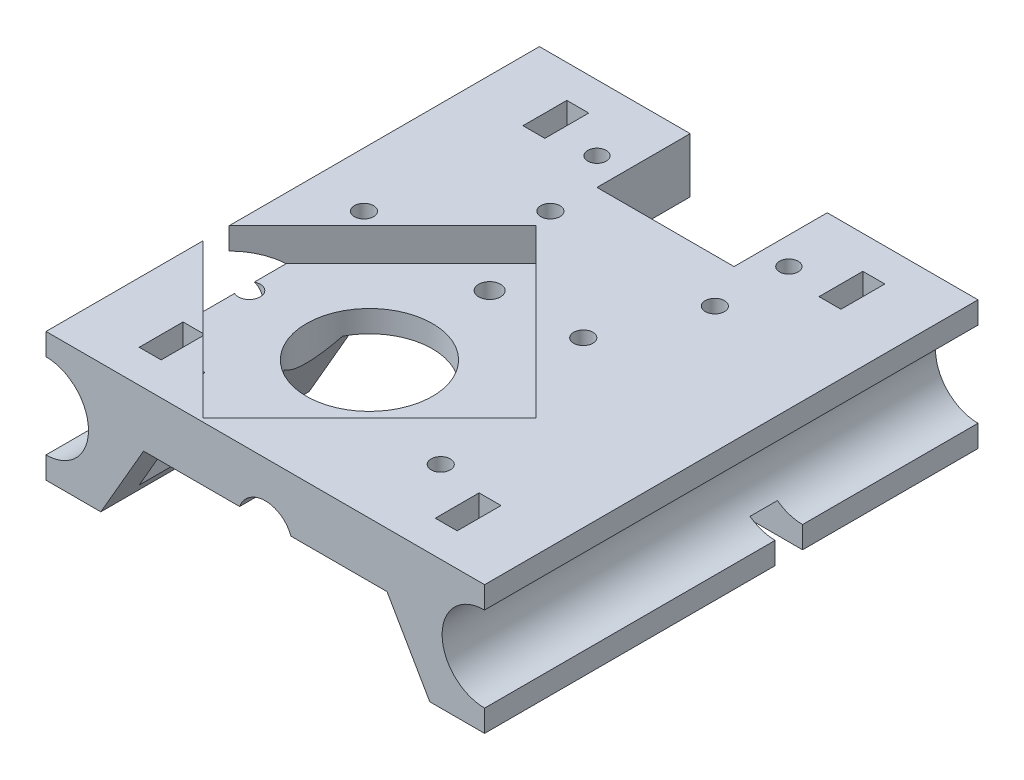
SolidWorks part; units mm, degrees
material "ABS"
ref_plane "Plano frontal" through (0, 0, 0) normal (0, 0, 1) x (1, 0, 0)
ref_plane "Plano superior" through (0, 0, 0) normal (0, 1, 0) x (1, 0, 0)
ref_plane "Plano direito" through (0, 0, 0) normal (1, 0, 0) x (0, 0, -1)
sketch "Esboço1" plane through (0, 0, 0) normal (0, 0, 1) x (1, 0, 0)
  line L0 (40, 0) -> (-40, 0)
  line L1 (-40, -19.5) -> (-40, -23.5)
  line L2 (-40, -23.5) -> (-30, -23.5)
  line L3 (-30, -23.5) -> (-22.2058, -10)
  line L4 (-22.2058, -10) -> (-4.6837, -10)
  line L5 (-40, 0) -> (-40, -4)
  line L6 (0, 0) -> (0, -46.1263) construction
  line L7 (40, 0) -> (40, -4)
  line L8 (30, -23.5) -> (22.2058, -10)
  line L9 (40, -23.5) -> (30, -23.5)
  line L10 (40, -19.5) -> (40, -23.5)
  line L11 (4.6837, -10) -> (22.2058, -10)
  line L12 (-40, -11.75) -> (40, -11.75) construction
  arc A0 (-40, -4) -> (-40, -19.5) centre (-40, -11.75) cw
  arc A1 (40, -4) -> (40, -19.5) centre (40, -11.75) ccw
  arc A2 (4.6837, -10) -> (-4.6837, -10) centre (0, -11.75) ccw
  point P17 (0, -12.2866)
  dimension "D1" = 7.75
  dimension "D7" = 5
  dimension "D2" = 4
  dimension "D3" = 60
  dimension "D4" = 10
  dimension "D5" = 10
  dimension "D6" = 40
extrude "Ressalto-extrusão1" add sketch "Esboço1" along normal blind 90
sketch "Esboço2" plane through (0, 0, 0) normal (0, 1, 0) x (1, 0, 0)
  line L1 (-42.4056, -59) -> (-12, -28.5944)
  line L2 (-42.4056, -59) -> (-12, -89.4056)
  line L3 (-12, -89.4056) -> (18.4056, -59)
  line L4 (-12, -28.5944) -> (18.4056, -59)
  line L5 (-42.4056, -59) -> (18.4056, -59) construction
  line L6 (-12, -89.4056) -> (-12, -28.5944) construction
  line L8 (-40, -90) -> (-40, 0) construction
  line L9 (40, -90) -> (-40, -90) construction
  line L11 (-22.2058, -90) -> (-4.6837, -90) construction
  circle A0 centre (-12, -59) radius 5
  point P0 (-12, -59)
  dimension "D4" = 10
  dimension "D1" = 43
  dimension "D2" = 28
  dimension "D3" = 31
extrude "Corte-extrusão1" cut sketch "Esboço2" against normal offset from surface (6 mm away) 4 up to face at (-13.4448, -10, 45)
sketch "Esboço3" plane through (0, -6, 0) normal (0, 1, 0) x (1, 0, 0)
  line L2 (-6.7523, -61.9088) -> (5.6269, -39.576) construction
  line L3 (-17.6288, -61.0776) -> (-25.3093, -40.2687) construction
  line L4 (-12, -37.0797) -> (9.9203, -59) construction
  line L5 (-12, -37.0797) -> (-33.9203, -59) construction
  line L6 (-33.9203, -59) -> (-12, -80.9203) construction
  line L7 (9.9203, -59) -> (-12, -80.9203) construction
  line L8 (-12, -37.0797) -> (-12, -80.9203) construction
  line L9 (-33.9203, -59) -> (9.9203, -59) construction
  line L10 (40, -90) -> (-40, -90) construction
  line L13 (-12, -28.5944) -> (-40, -56.5944) construction
  line L14 (4.6837, -90) -> (22.2058, -90) construction
  line L16 (-12.5, -17) -> (12.5, -17)
  line L17 (-12.5, -17) -> (-12.5, 0)
  line L18 (-12.5, 0) -> (12.5, 0)
  line L19 (12.5, -17) -> (12.5, 0)
  line L20 (-12.5, -17) -> (12.5, 0) construction
  line L21 (-12.5, 0) -> (12.5, -17) construction
  line L22 (0, -12.8859) -> (0, -1.9558) construction
  line L24 (18.4056, -59) -> (-12, -28.5944) construction
  circle A0 centre (-12, -37.0797) radius 2
  circle A1 centre (9.9203, -59) radius 2
  circle A2 centre (-12, -80.9203) radius 2
  circle A3 centre (-33.9203, -59) radius 2
  circle A4 centre (-12, -59) radius 11.5
  arc A5 (-17.6288, -61.0776) -> (-6.7523, -61.9088) centre (-12, -59) ccw construction
  circle A6 centre (-30, -42) radius 1.75
  circle A7 centre (10, -42) radius 1.75
  circle A8 centre (10, -42) radius 5 construction
  circle A9 centre (-30, -42) radius 5 construction
  circle A10 centre (-17.5, -12) radius 1.7
  circle A11 centre (17.5, -12) radius 1.7
  circle A12 centre (17, -75) radius 1.75
  circle A13 centre (-13, -25) radius 1.75
  circle A14 centre (17, -25) radius 1.75
  circle A15 centre (17, -25) radius 7.5 construction
  circle A16 centre (-13, -25) radius 7.5 construction
  circle A17 centre (17, -75) radius 7.5 construction
  point P0 (0, 0)
  point P6 (-12, -59)
  point P29 (0, 0)
  point P38 (0, -8.5)
  point P60 (17, -75)
  dimension "D3" = 23
  dimension "D4" = 12
  dimension "D5" = 3.5
  dimension "D8" = 10
  dimension "D12" = 3.4
  dimension "D13" = 3.5
  dimension "D17" = 15
  dimension "D19" = 4
  dimension "D2" = 31
  dimension "D6" = 48
  dimension "D7" = 40
  dimension "D9" = 17
  dimension "D10" = 25
  dimension "D11" = 17.5
  dimension "D14" = 15
  dimension "D15" = 30
  dimension "D16" = 50
  dimension "D18" = 22
  dimension "D20" = 17
  dimension "D21" = 31
  dimension "D22" = 7
  dimension "D23" = 17
  dimension "D24" = 5
extrude "Corte-extrusão2" cut sketch "Esboço3" against normal through all and the other way through all
sketch "Esboço4" plane through (0, -10, 0) normal (0, -1, 0) x (1, 0, 0)
  line L0 (-44.5112, 37) -> (44.1077, 37)
  line L2 (-44.5112, 37) -> (-44.5112, 32)
  line L3 (-44.5112, 32) -> (44.1077, 32)
  line L4 (44.1077, 32) -> (44.1077, 37)
  circle A0 centre (-30, 42) radius 5 construction
  circle A1 centre (10, 42) radius 5 construction
  point P11 (-28.4465, 37.2475)
  dimension "D1" = 10
  dimension "D2" = 5
extrude "Corte-extrusão4" cut sketch "Esboço4" against normal blind 12 from offset 20
sketch "Esboço6" plane through (0, -23.5, 0) normal (0, -1, 0) x (1, 0, 0)
  line L0 (-40, 90) -> (-40, 37) construction
  line L2 (-20, 32) -> (-40, 32)
  line L5 (-20, 32) -> (-20, 52)
  line L6 (-20, 52) -> (-40, 52)
  line L7 (-40, 32) -> (-40, 52)
  line L8 (-20, 32) -> (-40, 52) construction
  line L9 (-20, 52) -> (-40, 32) construction
  line L10 (-30, 32) -> (-40, 32) construction
  circle A0 centre (17, 75) radius 8
  circle A1 centre (17, 25) radius 8
  circle A2 centre (-13, 25) radius 8
  point P0 (-30, 42)
  dimension "D1" = 16
extrude "Corte-extrusão7" cut sketch "Esboço6" against normal up to surface (13.5 mm away) up to face at (-14, -10, 80.9203)
sketch "Esboço7" plane through (0, 0, 0) normal (0, 1, 0) x (1, 0, 0)
  line L0 (-32.25, 0) -> (-32.25, -90) construction
  line L1 (40, -90) -> (-40, -90) construction
  line L3 (32.25, -90) -> (32.25, 0) construction
  line L5 (27.0009, -70) -> (27.0009, -90) construction
  line L6 (40, -90) -> (-40, -90) construction
  line L7 (44.8347, -45) -> (-53.0929, -45) construction
  line L8 (25.0009, -76) -> (29.0009, -76)
  line L9 (25.0009, -76) -> (25.0009, -84)
  line L10 (25.0009, -84) -> (29.0009, -84)
  line L11 (29.0009, -76) -> (29.0009, -84)
  line L12 (25.0009, -76) -> (29.0009, -84) construction
  line L13 (25.0009, -84) -> (29.0009, -76) construction
  line L14 (25.0009, -6) -> (29.0009, -14) construction
  line L15 (25.0009, -14) -> (29.0009, -6) construction
  line L16 (27.0009, -20) -> (27.0009, 0) construction
  line L17 (29.0009, -14) -> (29.0009, -6)
  line L18 (25.0009, -6) -> (29.0009, -6)
  line L19 (25.0009, -14) -> (25.0009, -6)
  line L20 (25.0009, -14) -> (29.0009, -14)
  line L21 (0, 4.9721) -> (0, -101.7412) construction
  line L22 (-27.0009, -20) -> (-27.0009, 0) construction
  line L23 (-25.0009, -14) -> (-29.0009, -6) construction
  line L24 (-25.0009, -6) -> (-29.0009, -14) construction
  line L25 (-25.0009, -84) -> (-29.0009, -76) construction
  line L26 (-25.0009, -76) -> (-29.0009, -84) construction
  line L27 (-27.0009, -70) -> (-27.0009, -90) construction
  line L28 (-25.0009, -14) -> (-29.0009, -14)
  line L29 (-25.0009, -14) -> (-25.0009, -6)
  line L30 (-25.0009, -6) -> (-29.0009, -6)
  line L31 (-29.0009, -14) -> (-29.0009, -6)
  line L32 (-29.0009, -76) -> (-29.0009, -84)
  line L33 (-25.0009, -84) -> (-29.0009, -84)
  line L34 (-25.0009, -76) -> (-25.0009, -84)
  line L35 (-25.0009, -76) -> (-29.0009, -76)
  point P10 (27.0009, -80)
  point P27 (27.0009, -10)
  point P43 (-27.0009, -10)
  point P44 (-27.0009, -80)
  dimension "D1" = 20
  dimension "D2" = 8
  dimension "D3" = 4
extrude "Corte-extrusão8" cut sketch "Esboço7" against normal through all
sketch "Esboço11" plane through (0, -10, 0) normal (0, -1, 0) x (1, 0, 0)
  circle A0 centre (-13, 25) radius 3.5
  circle A1 centre (-13, 25) radius 1.75
  circle A2 centre (17, 25) radius 1.75
  circle A3 centre (17, 25) radius 3.5
  circle A4 centre (17, 75) radius 3.5
  circle A5 centre (17, 75) radius 1.75
  dimension "D1" = 7
extrude "Ressalto-extrusão3" add sketch "Esboço11" along normal blind 12
